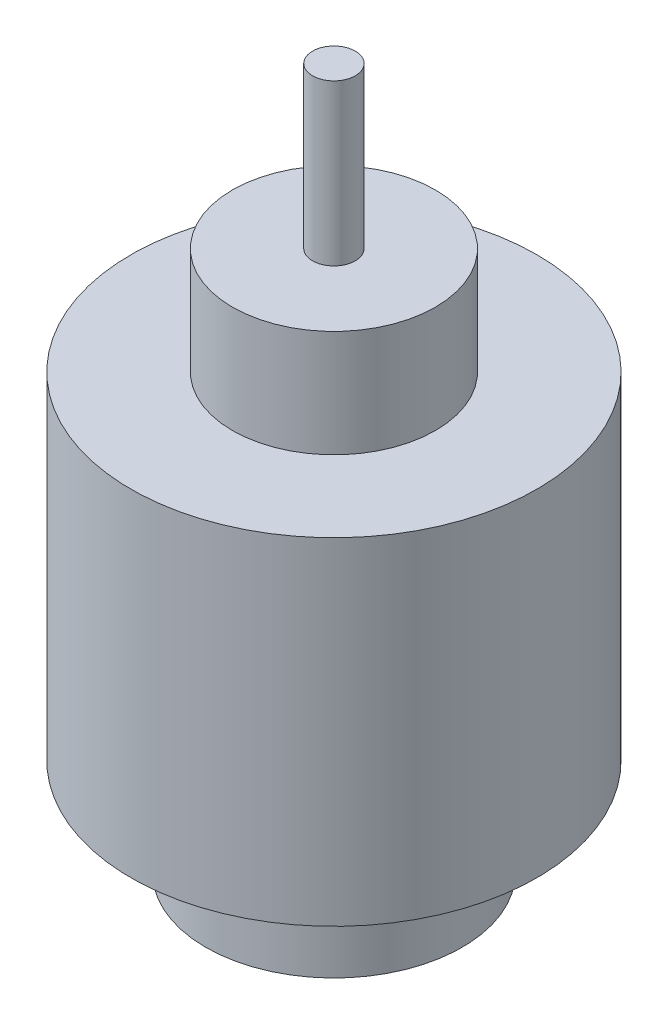
SolidWorks part; units mm, degrees
ref_plane "Front" through (0, 0, 0) normal (0, 0, 1) x (1, 0, 0)
ref_plane "Top" through (0, 0, 0) normal (0, 1, 0) x (1, 0, 0)
ref_plane "Right" through (0, 0, 0) normal (1, 0, 0) x (0, 0, -1)
sketch "Sketch2" plane through (0, 0, 0) normal (0, 0, 1) x (1, 0, 0)
  line L0 (0, 0) -> (0, 70)
  line L1 (0, 70) -> (2, 70)
  line L2 (2, 70) -> (2, 55)
  line L3 (2, 55) -> (9.5, 55)
  line L4 (9.5, 55) -> (9.5, 45)
  line L5 (9.5, 45) -> (19, 45)
  line L6 (19, 45) -> (19, 13.5072)
  line L7 (19, 13.5072) -> (12, 13.5072)
  line L8 (12, 13.5072) -> (12, 4.3706)
  line L9 (12, 4.3706) -> (3.4841, 4.3706)
  line L10 (3.4841, 4.3706) -> (3.4841, 0)
  line L11 (3.4841, 0) -> (0, 0)
  point P15 (1.7914, 70)
  dimension "D1" = 55
  dimension "D2" = 19
  dimension "D3" = 9.5
  dimension "D4" = 12
  dimension "D5" = 15
  dimension "D6" = 2
  dimension "D7" = 10
revolve "Revolve1" add sketch "Sketch2" angle 360 about L0
